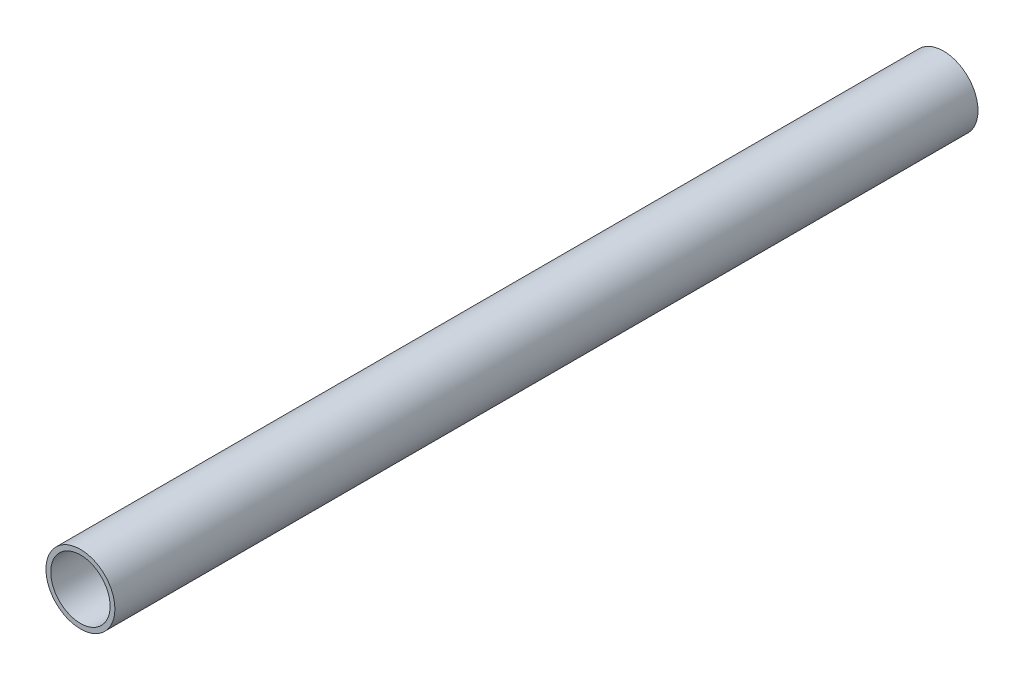
SolidWorks part; units mm, degrees
ref_plane "前视基准面" through (0, 0, 0) normal (0, 0, 1) x (1, 0, 0)
ref_plane "上视基准面" through (0, 0, 0) normal (0, 1, 0) x (1, 0, 0)
ref_plane "右视基准面" through (0, 0, 0) normal (1, 0, 0) x (0, 0, -1)
sketch "草图1" plane through (0, 0, 0) normal (0, 0, 1) x (1, 0, 0)
  circle A0 centre (0, 0) radius 7.55
  circle A1 centre (0, 0) radius 6.5
  dimension "D1" = 15.1
  dimension "D2" = 13
extrude "凸台-拉伸1" add sketch "草图1" along normal blind 189
